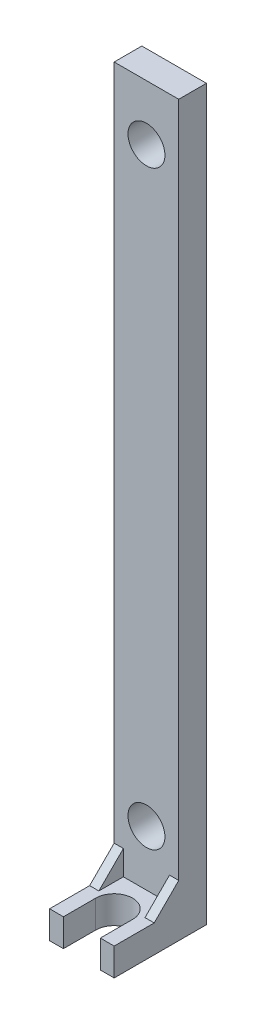
SolidWorks part; units mm, degrees
ref_plane "Front Plane" through (0, 0, 0) normal (0, 0, 1) x (1, 0, 0)
ref_plane "Top Plane" through (0, 0, 0) normal (0, 1, 0) x (1, 0, 0)
ref_plane "Right Plane" through (0, 0, 0) normal (1, 0, 0) x (0, 0, -1)
sketch "Sketch1" plane through (0, 0, 0) normal (0, 0, 1) x (1, 0, 0)
  line L1 (-3.5, 39.5) -> (3.5, 39.5)
  line L2 (-3.5, 39.5) -> (-3.5, -39.5)
  line L3 (-3.5, -39.5) -> (3.5, -39.5)
  line L4 (3.5, 39.5) -> (3.5, -39.5)
  line L5 (-3.5, 39.5) -> (3.5, -39.5) construction
  line L6 (-3.5, -39.5) -> (3.5, 39.5) construction
  circle A0 centre (0, -30.5) radius 2
  circle A1 centre (0, 33.5) radius 2
  point P0 (0, 0)
  dimension "D3" = 4
  dimension "D5" = 4
  dimension "D1" = 7
  dimension "D2" = 79
  dimension "D4" = 9
  dimension "D6" = 64
extrude "Boss-Extrude1" add sketch "Sketch1" along normal blind 3
sketch "Sketch2" plane through (0, 0, 3) normal (0, 0, 1) x (1, 0, 0)
  line L0 (3.5, -39.5) -> (3.5, 39.5) construction
  line L1 (-3.5, -36.5) -> (3.5, -36.5)
  line L2 (-3.5, -36.5) -> (-3.5, -39.5)
  line L3 (-3.5, -39.5) -> (3.5, -39.5)
  line L4 (3.5, -36.5) -> (3.5, -39.5)
  line L5 (-3.5, -36.5) -> (3.5, -39.5) construction
  line L6 (-3.5, -39.5) -> (3.5, -36.5) construction
  line L7 (-3.5, -39.5) -> (3.5, -39.5) construction
  point P0 (0, -38)
  dimension "D1" = 3
extrude "Boss-Extrude2" add sketch "Sketch2" along normal blind 7
sketch "Sketch3" plane through (0, -39.5, 0) normal (0, -1, 0) x (1, 0, 0)
  line L0 (-3.5, 10) -> (3.5, 10) construction
  line L1 (-2, 6.5) -> (-2, 10)
  line L2 (2, 6.5) -> (2, 10)
  line L3 (-2, 10) -> (2, 10)
  arc A0 (-2, 6.5) -> (2, 6.5) centre (0, 6.5) ccw
  dimension "D1" = 4
  dimension "D2" = 3.5
extrude "Cut-Extrude1" cut sketch "Sketch3" against normal up to next
sketch "Sketch4" plane through (-3.5, 0, 0) normal (-1, 0, 0) x (0, 0, 1)
  line L0 (3, -33.8395) -> (5.6605, -36.5)
  line L1 (3, 39.5) -> (3, -36.5) construction
  line L2 (10, -36.5) -> (3, -36.5) construction
  line L3 (3, -33.8395) -> (3, -36.5)
  line L4 (3, -36.5) -> (5.6605, -36.5)
extrude "Boss-Extrude3" add sketch "Sketch4" against normal blind 1
ref_plane "Plane1" through (0, 0, 0) normal (-1, 0, 0) x (0, 0, 1)
mirror "Mirror1" about plane through (0, 0, 0) normal (-1, 0, 0) of "Boss-Extrude3"
